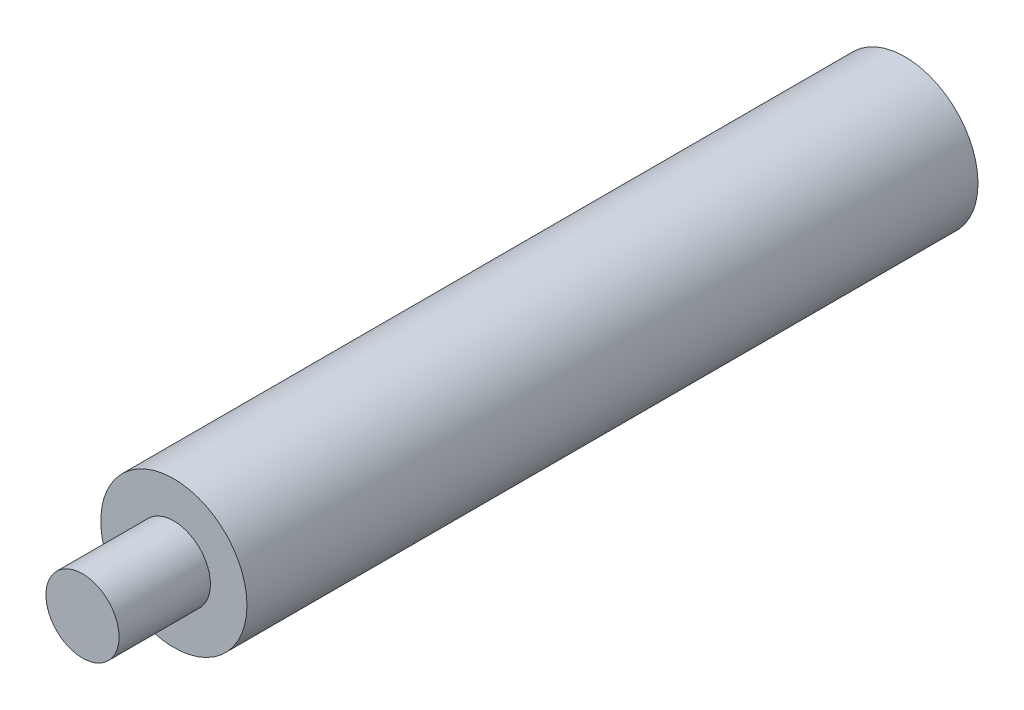
SolidWorks part; units mm, degrees
ref_plane "Front Plane" through (0, 0, 0) normal (0, 0, 1) x (1, 0, 0)
ref_plane "Top Plane" through (0, 0, 0) normal (0, 1, 0) x (1, 0, 0)
ref_plane "Right Plane" through (0, 0, 0) normal (1, 0, 0) x (0, 0, -1)
sketch "Sketch1" plane through (0, 0, 0) normal (0, 0, 1) x (1, 0, 0)
  circle A0 centre (0, 0) radius 40
extrude "Boss-Extrude1" add sketch "Sketch1" along normal blind 400 contours A0
sketch "Sketch2" plane through (0, 0, 400) normal (0, 0, 1) x (1, 0, 0)
  circle A0 centre (0, 0) radius 20
extrude "Boss-Extrude2" add sketch "Sketch2" along normal blind 50 contours A0
